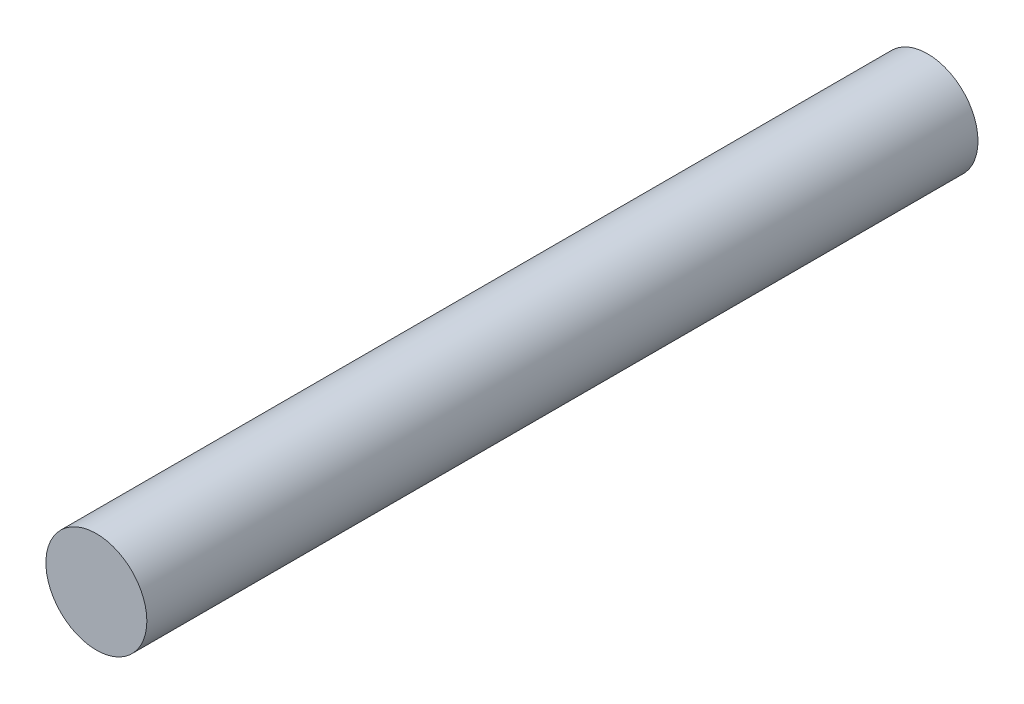
SolidWorks part; units mm, degrees
ref_plane "Front Plane" through (0, 0, 0) normal (0, 0, 1) x (1, 0, 0)
ref_plane "Top Plane" through (0, 0, 0) normal (0, 1, 0) x (1, 0, 0)
ref_plane "Right Plane" through (0, 0, 0) normal (1, 0, 0) x (0, 0, -1)
sketch "Sketch1" plane through (0, 0, 0) normal (0, 0, 1) x (1, 0, 0)
  circle A0 centre (0, 0) radius 8.89
  dimension "D1" = 17.78
extrude "Boss-Extrude1" add sketch "Sketch1" along normal blind 33.2 and the other way blind 113.2
